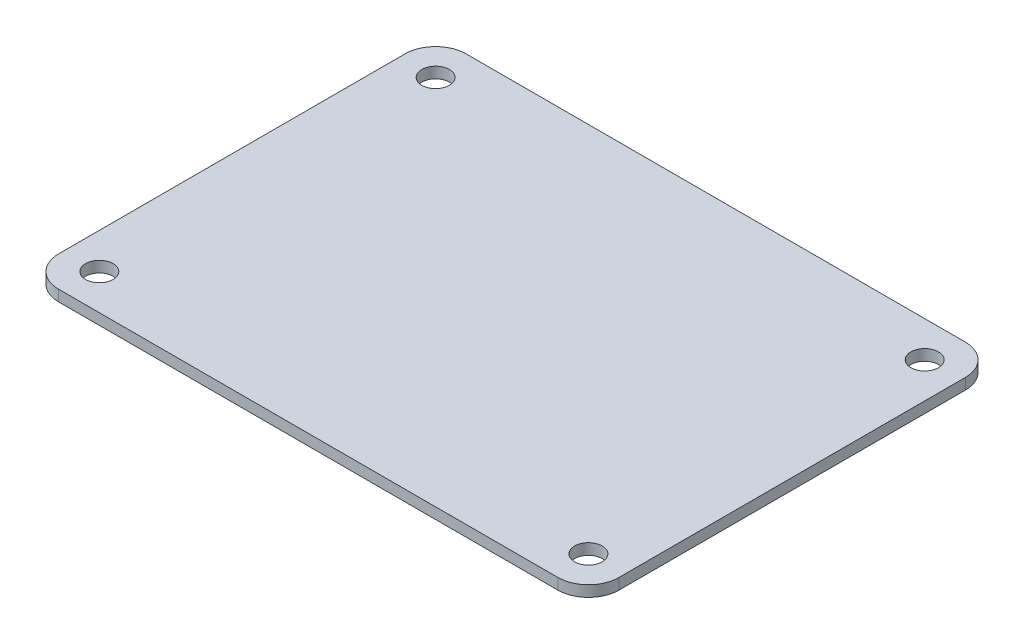
SolidWorks part; units mm, degrees
ref_plane "Front Plane" through (0, 0, 0) normal (0, 0, 1) x (1, 0, 0)
ref_plane "Top Plane" through (0, 0, 0) normal (0, 1, 0) x (1, 0, 0)
ref_plane "Right Plane" through (0, 0, 0) normal (1, 0, 0) x (0, 0, -1)
sketch "Sketch1" plane through (0, 0, 0) normal (0, 1, 0) x (1, 0, 0)
  line L1 (-24.5, -20) -> (24.5, -20)
  line L2 (-27.5, -17) -> (-27.5, 17)
  line L3 (-24.5, 20) -> (24.5, 20)
  line L4 (27.5, -17) -> (27.5, 17)
  line L5 (-27.5, -20) -> (27.5, 20) construction
  line L6 (-27.5, 20) -> (27.5, -20) construction
  circle A0 centre (-24, 16.5) radius 1.35
  circle A1 centre (-24, -16.5) radius 1.35
  circle A2 centre (24, 16.5) radius 1.35
  circle A3 centre (24, -16.5) radius 1.35
  arc A4 (-24.5, -20) -> (-27.5, -17) centre (-24.5, -17) cw
  arc A5 (24.5, -20) -> (27.5, -17) centre (24.5, -17) ccw
  arc A6 (24.5, 20) -> (27.5, 17) centre (24.5, 17) cw
  arc A7 (-27.5, 17) -> (-24.5, 20) centre (-24.5, 17) cw
  point P0 (0, 0)
  dimension "D3" = 2.7
  dimension "D8" = 3
  dimension "D1" = 55
  dimension "D2" = 40
  dimension "D4" = 3.5
  dimension "D5" = 3.5
  dimension "D6" = 3.5
  dimension "D7" = 3.5
extrude "Boss-Extrude1" add sketch "Sketch1" along normal blind 1.08
